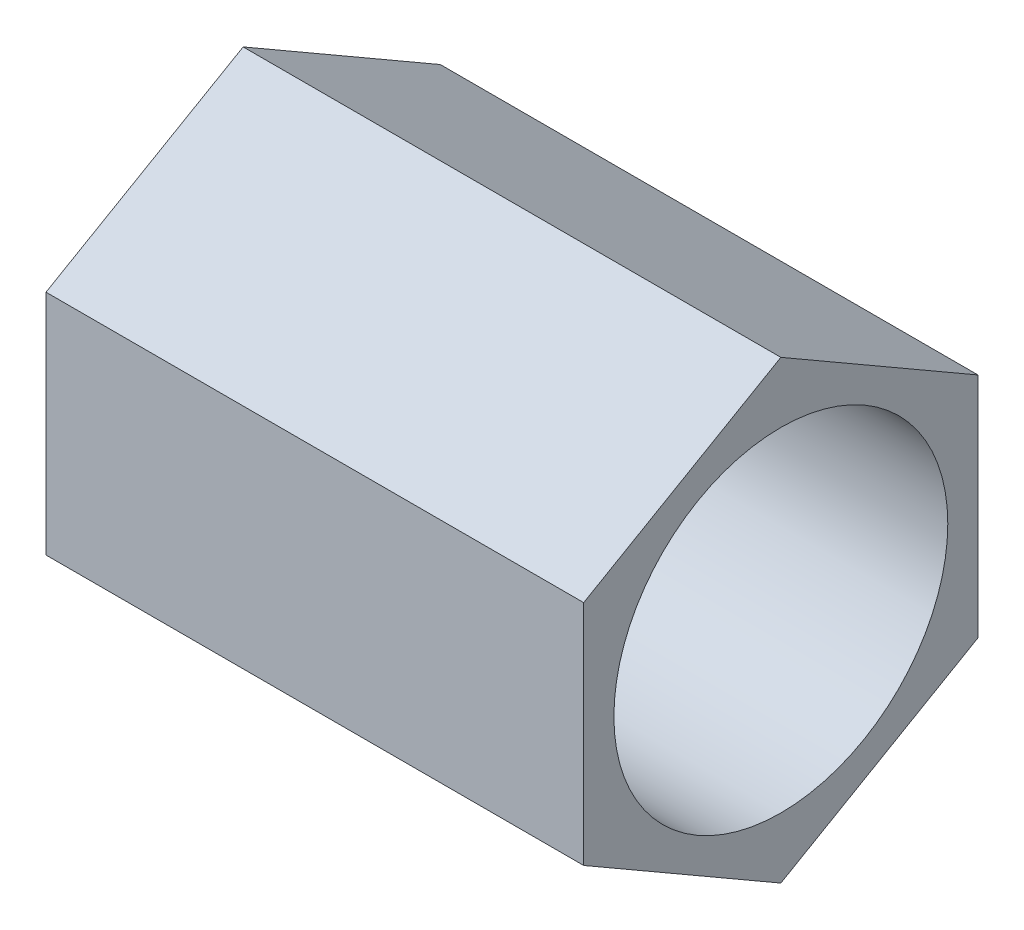
SolidWorks part; units mm, degrees
material "V4a"
ref_plane "Vorne" through (0, 0, 0) normal (0, 0, 1) x (1, 0, 0)
ref_plane "Oben" through (0, 0, 0) normal (0, 1, 0) x (1, 0, 0)
ref_plane "Rechts" through (0, 0, 0) normal (1, 0, 0) x (0, 0, -1)
sketch "Skizze2" plane through (0, 0, 0) normal (0, 0, 1) x (1, 0, 0)
  line L0 (-12.8257, 0) -> (37.1476, 0) construction
  line L1 (0, 0) -> (0, 3.1426) construction
  line L2 (-15, 13.5) -> (-14.5981, 15)
  line L3 (-14.5981, 15) -> (14.5981, 15)
  line L4 (14.5981, 15) -> (15, 13.5)
  line L5 (15, 13.5) -> (15, 9.315)
  line L6 (15, 9.315) -> (-15, 9.315)
  line L7 (-15, 13.5) -> (-15, 9.315)
  point P5 (0, 9.315)
  dimension "D1" = 30
  dimension "D2" = 30
  dimension "D3" = 27
  dimension "D4" = 15
  dimension "D9" = 18.63
revolve "Rotation1" add sketch "Skizze2" angle 360 about L0
sketch "Skizze3" plane through (0, 0, 0) normal (1, 0, 0) x (0, 0, -1)
  line L0 (11, 10.198) -> (11, -10.198)
  circle A0 centre (0, 0) radius 15 construction
  arc A1 (11, -10.198) -> (11, 10.198) centre (0, 0) ccw
  dimension "D1" = 11
extrude "Schnitt-Linear austragen2" cut sketch "Skizze3" along normal through all and the other way through all
pattern_circular "Kreismuster1" count 6 over 360 about axis through (0, 0, 0) along (1, 0, 0) of "Schnitt-Linear austragen2"
